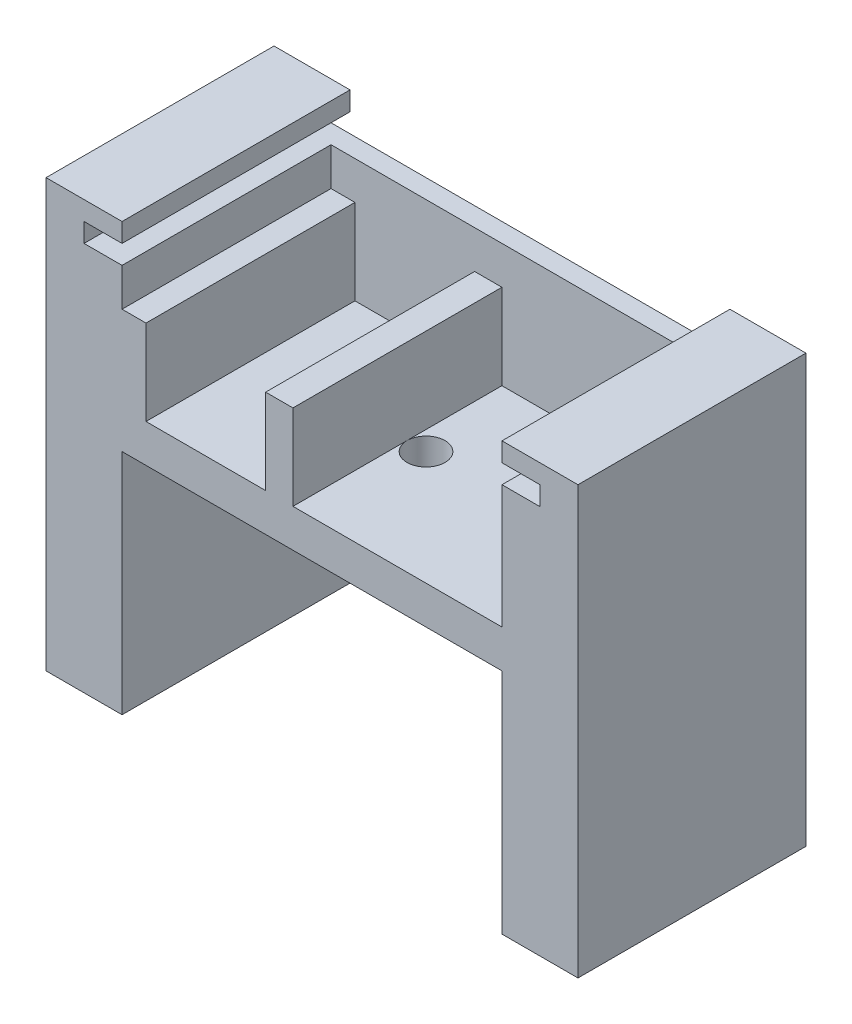
SolidWorks part; units mm, degrees
ref_plane "Front Plane" through (0, 0, 0) normal (0, 0, 1) x (1, 0, 0)
ref_plane "Top Plane" through (0, 0, 0) normal (0, 1, 0) x (1, 0, 0)
ref_plane "Right Plane" through (0, 0, 0) normal (1, 0, 0) x (0, 0, -1)
sketch "Sketch1" plane through (0, 0, 0) normal (0, 0, 1) x (1, 0, 0)
  line L0 (-63.5, 0) -> (63.5, 0)
  line L1 (-63.5, 0) -> (-63.5, -76.2)
  line L2 (63.5, 0) -> (63.5, -76.2)
  line L3 (63.5, -76.2) -> (88.9, -76.2)
  line L4 (-63.5, -76.2) -> (-88.9, -76.2)
  line L5 (-88.9, -76.2) -> (-88.9, 66.6)
  line L6 (-88.9, 66.6) -> (-63.5, 66.6)
  line L7 (-63.5, 66.6) -> (-63.5, 60.25)
  line L8 (-63.5, 60.25) -> (-76.2, 60.25)
  line L9 (-76.2, 60.25) -> (-76.2, 53.9)
  line L10 (-76.2, 53.9) -> (-63.5, 53.9)
  line L11 (-63.5, 53.9) -> (-63.5, 41.2)
  line L12 (-63.5, 41.2) -> (-55.5, 41.2)
  line L13 (-55.5, 41.2) -> (-55.5, 12.7)
  line L14 (-55.5, 12.7) -> (-15.5, 12.7)
  line L15 (-15.5, 12.7) -> (-15.5, 41.2)
  line L16 (-15.5, 41.2) -> (-6.3715, 41.2)
  line L17 (-6.3715, 41.2) -> (-6.3715, 12.7)
  line L18 (-6.3715, 12.7) -> (63.5, 12.7)
  line L20 (63.5, 66.6) -> (88.9, 66.6)
  line L21 (88.9, 66.6) -> (88.9, -76.2)
  line L22 (63.5, 66.6) -> (63.5, 60.25)
  line L23 (63.5, 60.25) -> (76.2, 60.25)
  line L24 (76.2, 60.25) -> (76.2, 53.9)
  line L25 (76.2, 53.9) -> (63.5, 53.9)
  line L26 (63.5, 53.9) -> (63.5, 12.7)
  point P4 (0, 0)
  point P28 (0, 0)
  dimension "D1" = 127
  dimension "D2" = 76.2
  dimension "D3" = 25.4
  dimension "D4" = 25.4
  dimension "D5" = 142.8
  dimension "D6" = 25.4
  dimension "D7" = 6.35
  dimension "D8" = 6.35
  dimension "D9" = 12.7
  dimension "D10" = 12.7
  dimension "D11" = 12.7
  dimension "D12" = 28.5
  dimension "D13" = 8
  dimension "D14" = 40
  dimension "D15" = 28.5
  dimension "D16" = 12.7
extrude "Boss-Extrude1" add sketch "Sketch1" along normal blind 76.2
sketch "Sketch2" plane through (63.5, 0, 0) normal (-1, 0, 0) x (0, 0, 1)
  line L0 (76.2, 12.7) -> (0, 12.7) construction
  line L1 (0, 53.9) -> (6.35, 53.9)
  line L2 (0, 53.9) -> (0, 12.7)
  line L3 (0, 12.7) -> (6.35, 12.7)
  line L4 (6.35, 53.9) -> (6.35, 12.7)
  dimension "D1" = 6.35
extrude "Boss-Extrude2" add sketch "Sketch2" along normal up to vertex (127 mm away) up to point (-63.5, 53.9, 76.2)
sketch "Sketch3" plane through (0, 0, 0) normal (0, -1, 0) x (1, 0, 0)
  circle A0 centre (0, 38.1) radius 6.35
  dimension "D1" = 12.7
extrude "Cut-Extrude1" cut sketch "Sketch3" against normal blind 105.2
